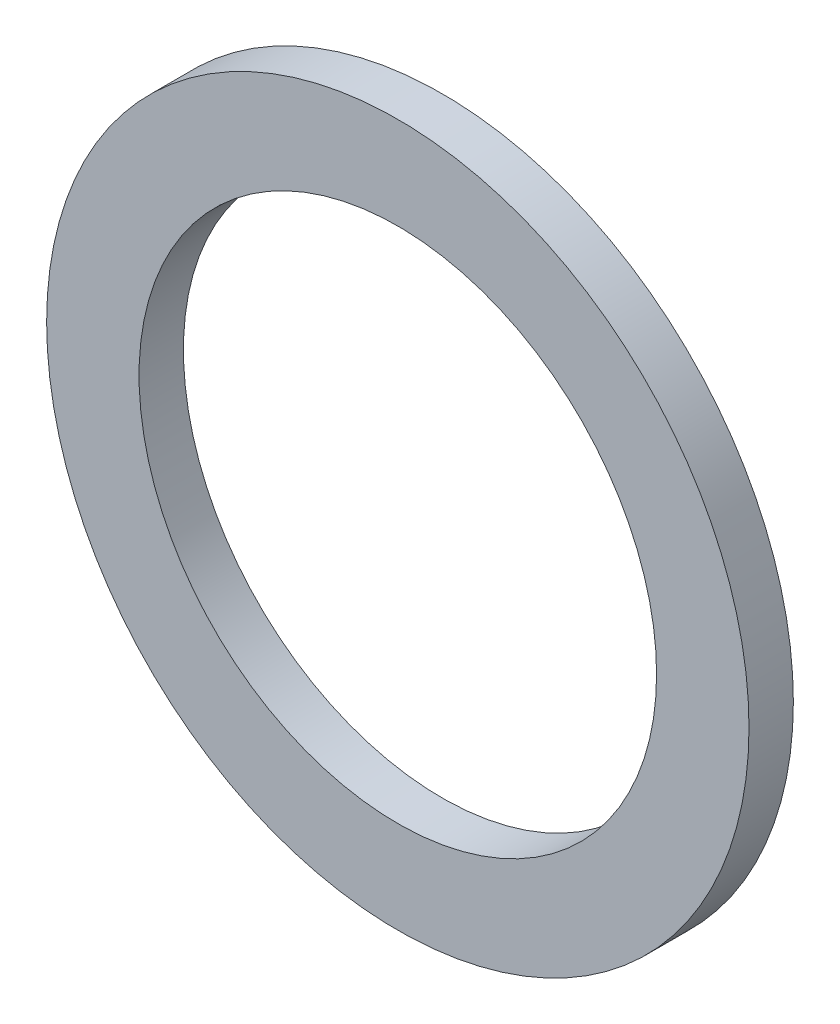
SolidWorks part; units mm, degrees
ref_plane "前视基准面" through (0, 0, 0) normal (0, 0, 1) x (1, 0, 0)
ref_plane "上视基准面" through (0, 0, 0) normal (0, 1, 0) x (1, 0, 0)
ref_plane "右视基准面" through (0, 0, 0) normal (1, 0, 0) x (0, 0, -1)
sketch "草图1" plane through (0, 0, 0) normal (0, 0, 1) x (1, 0, 0)
  circle A0 centre (0, 0) radius 35
  circle A1 centre (0, 0) radius 47.5
  dimension "D1" = 95
  dimension "D2" = 70
extrude "凸台-拉伸1" add sketch "草图1" along normal blind 6
